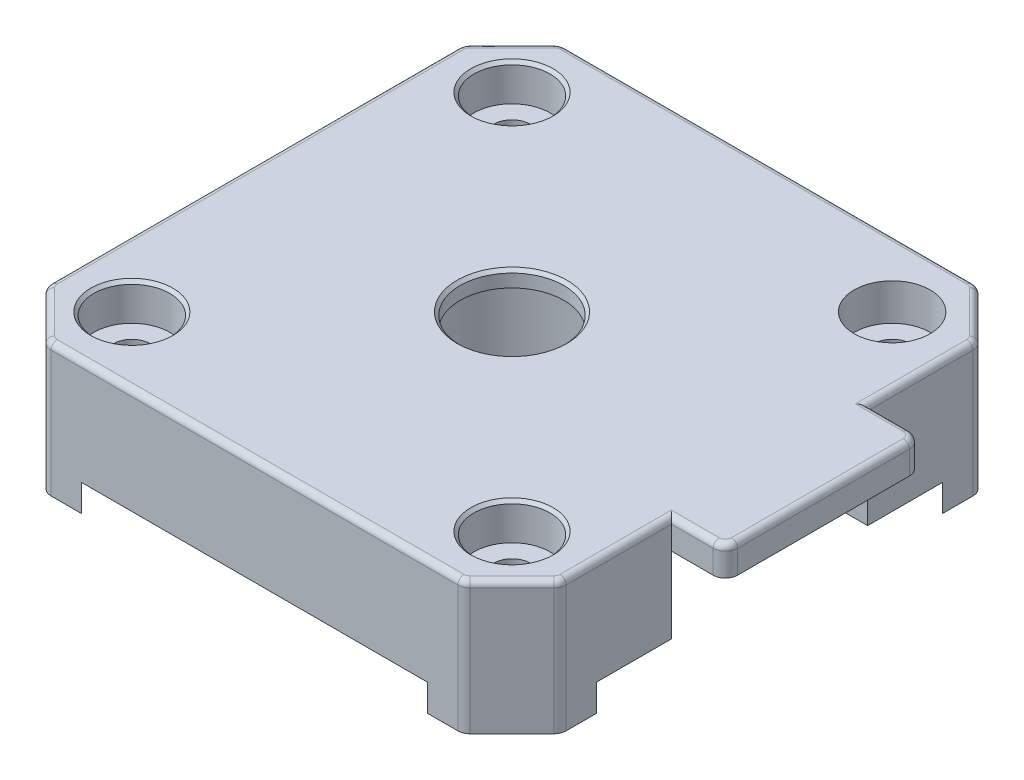
SolidWorks part; units mm, degrees
ref_plane "Alzado" through (0, 0, 0) normal (0, 0, 1) x (1, 0, 0)
ref_plane "Planta" through (0, 0, 0) normal (0, 1, 0) x (1, 0, 0)
ref_plane "Vista lateral" through (0, 0, 0) normal (1, 0, 0) x (0, 0, -1)
sketch "Croquis1" plane through (0, 0, 0) normal (0, 1, 0) x (1, 0, 0)
  line L0 (21, -17) -> (21, 17)
  line L1 (21, 17) -> (17, 21)
  line L2 (17, 21) -> (-17, 21)
  line L3 (-17, 21) -> (-21, 17)
  line L4 (-21, 17) -> (-21, -17)
  line L5 (-21, -17) -> (-17, -21)
  line L6 (-17, -21) -> (17, -21)
  line L7 (17, -21) -> (21, -17)
extrude "Saliente-Extruir1" add sketch "Croquis1" against normal blind 10.8
sketch "Croquis2" plane through (0, -10.8, 0) normal (0, -1, 0) x (1, 0, 0)
  line L0 (-21, 17) -> (-21, -14.1008)
  line L1 (-21, -14.1008) -> (-14.1008, -21)
  line L2 (-14.1008, -21) -> (14.1008, -21)
  line L3 (14.1008, -21) -> (21, -14.1008)
  line L4 (21, -14.1008) -> (21, 17)
  line L5 (21, 17) -> (17, 21)
  line L6 (17, 21) -> (-17, 21)
  line L7 (-17, 21) -> (-21, 17)
extrude "Cortar-Extruir1" cut sketch "Croquis2" against normal blind 2.2
sketch "Croquis3" plane through (0, -8.6, 0) normal (0, -1, 0) x (1, 0, 0)
  line L0 (-21, 17) -> (-17, 21)
  line L1 (-17, 21) -> (-14.1008, 21)
  line L2 (-14.1008, 21) -> (-21, 14.1008)
  line L3 (-21, 14.1008) -> (-21, 17)
extrude "Saliente-Extruir2" add sketch "Croquis3" along normal blind 2.2
sketch "Croquis4" plane through (0, -8.6, 0) normal (0, -1, 0) x (1, 0, 0)
  line L0 (21, 17) -> (21, 14.1008)
  line L1 (21, 14.1008) -> (14.1008, 21)
  line L2 (14.1008, 21) -> (17, 21)
  line L3 (17, 21) -> (21, 17)
extrude "Saliente-Extruir3" add sketch "Croquis4" along normal blind 2.2
sketch "Croquis5" plane through (21, 0, 0) normal (1, 0, 0) x (0, 0, -1)
  line L0 (8, -2.4) -> (-8, -2.4)
  line L1 (-8, -2.4) -> (-8, 0)
  line L2 (-8, 0) -> (8, 0)
  line L3 (8, 0) -> (8, -2.4)
extrude "Saliente-Extruir4" add sketch "Croquis5" along normal blind 4.4
sketch "Croquis6" plane through (21, 0, 0) normal (1, 0, 0) x (0, 0, -1)
  line L0 (-8, -8.6) -> (8, -8.6)
  line L1 (8, -8.6) -> (8, -2.4)
  line L2 (8, -2.4) -> (-8, -2.4)
  line L3 (-8, -2.4) -> (-8, -8.6)
extrude "Cortar-Extruir2" cut sketch "Croquis6" against normal blind 21
hole_wizard "Refrentado para perno con cabeza hexagonal de M81" positions "Croquis8" profile "Croquis7" counterbore size "M8" standard "Ansi Metric"
sketch "Croquis8" plane through (0, -8.6, 0) normal (0, -1, 0) x (-1, 0, 0)
  point P0 (0, 0)
sketch "Croquis7" plane through (0, -8.6, 0) normal (1, 0, 0) x (0, 0, -1)
  line L0 (0, 0) -> (0, 8.6)
  line L1 (0, 8.6) -> (4.225, 8.6)
  line L3 (4.225, 8.6) -> (4.225, 7.3)
  line L4 (4.225, 7.3) -> (7.5, 7.3)
  line L5 (7.5, 7.3) -> (7.5, 0)
  line L7 (7.5, 0) -> (0, 0)
  line L11 (0, -6.35) -> (0, 107.95) construction
  dimension "Diámetro de taladro hasta el siguiente" = 8.45
  dimension "Profundidad de taladro hasta el siguiente" = 8.6
  dimension "Diámetro de refrentado" = 15
  dimension "Profundidad de refrentado" = 7.3
hole_wizard "Refrentado para tornillo con cabeza hexagonal de M2.51" positions "Croquis10" profile "Croquis9" counterbore size "M2.5" standard "Ansi Metric"
sketch "Croquis10" plane through (0, 0, 0) normal (0, 1, 0) x (1, 0, 0)
  point P0 (15.5, -15.5)
  point P1 (-15.5, -15.5)
  point P2 (-15.5, 15.5)
  point P3 (15.5, 15.5)
sketch "Croquis9" plane through (15.5, 0, 15.5) normal (1, 0, 0) x (0, 0, 1)
  line L0 (0, 0) -> (0, 10.8)
  line L1 (0, 10.8) -> (1.5, 10.8)
  line L3 (1.5, 10.8) -> (1.5, 3)
  line L4 (1.5, 3) -> (3.1, 3)
  line L5 (3.1, 3) -> (3.1, 0)
  line L7 (3.1, 0) -> (0, 0)
  line L11 (0, -6.35) -> (0, 107.95) construction
  dimension "Diámetro de taladro hasta el siguiente" = 3
  dimension "Profundidad de taladro hasta el siguiente" = 10.8
  dimension "Diámetro de refrentado" = 6.2
  dimension "Profundidad de refrentado" = 3
fillet "Redondeo1" radius 1 10 edges at (-21, -5.4, -17) (-17, -5.4, -21) (17, -5.4, -21) (21, -5.4, -17) (21, -5.4, 17) (-21, -5.4, 17) (-17, -5.4, 21) (17, -5.4, 21) (25.4, -1.2, -8) (25.4, -1.2, 8)
chamfer "Chaflán1" distance 0.25 angle 45 4 edges at (0, 0, -4.225) (-15.5, 0, -12.4) (-15.5, 0, 18.6) (15.5, 0, 18.6)
fillet "Redondeo2" radius 0.5 22 edges at (25.4, 0, 0) (19, 0, 19) (21, 0, 12.2929) (22.7, 0, 8) (22.7, 0, -8) (19, 0, -19) (0, 0, -21) (-19, 0, -19) (-21, 0, 0) (-19, 0, 19) (0, 0, 21) (20.9239, 0, 16.9685) (20.9239, 0, -16.9685) (-20.9239, 0, -16.9685) (16.9685, 0, 20.9239) (16.9685, 0, -20.9239) (-16.9685, 0, 20.9239) (-16.9685, 0, -20.9239) (25.1071, 0, 7.7071) (-20.9239, 0, 16.9685) (25.1071, 0, -7.7071) (21, 0, -12.2929)
